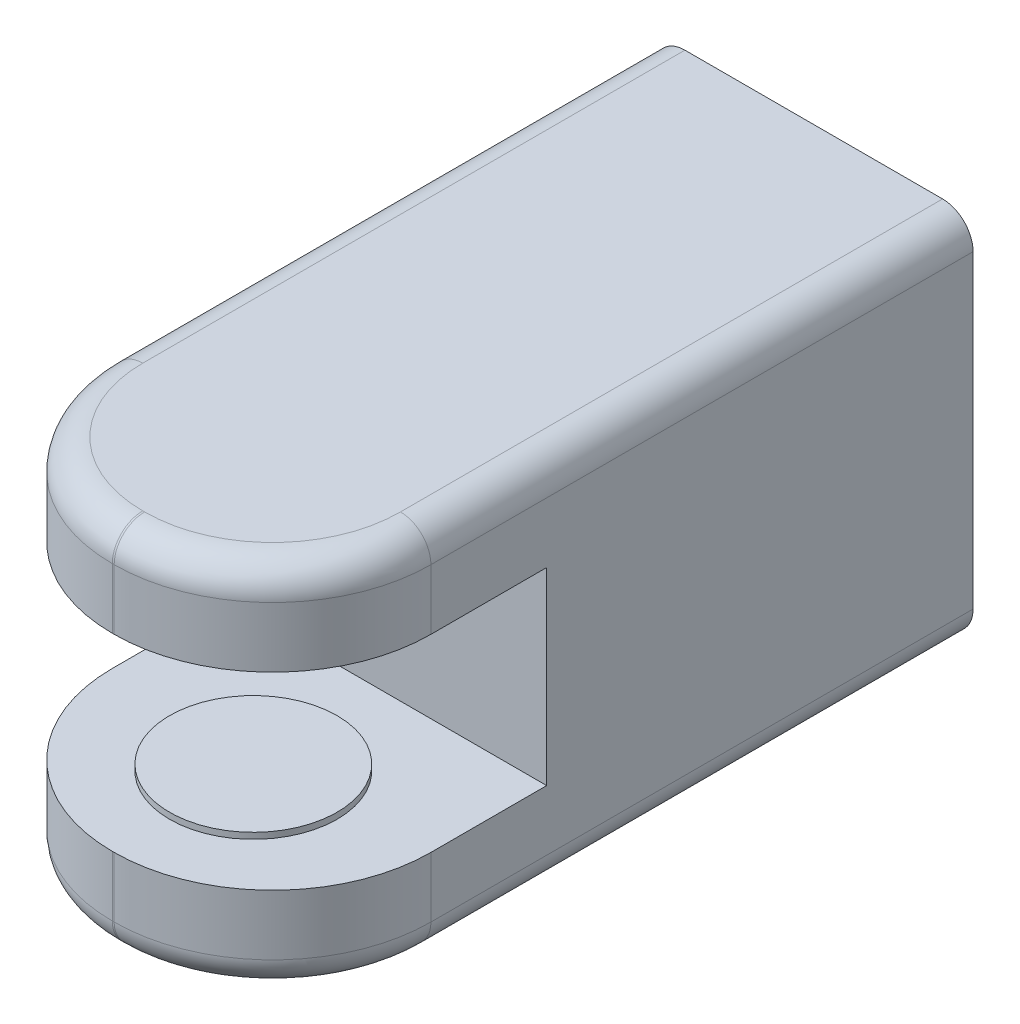
SolidWorks part; units mm, degrees
ref_plane "Piano frontale" through (0, 0, 0) normal (0, 0, 1) x (1, 0, 0)
ref_plane "Piano superiore" through (0, 0, 0) normal (0, 1, 0) x (1, 0, 0)
ref_plane "Piano destro" through (0, 0, 0) normal (1, 0, 0) x (0, 0, -1)
ref_plane "PianoContatto" through (0, 0, 0) normal (0, 0, 1) x (1, 0, 0)
sketch "Schizzo4" plane through (0, 0, 0) normal (0, 0, 1) x (1, 0, 0)
  circle A0 centre (0, 0) radius 38.5
  dimension "D1" = 77
extrude "CorpoContatto" add sketch "Schizzo4" along normal blind 3
sketch "Schizzo5" plane through (0, 0, 0) normal (0, 1, 0) x (1, 0, 0)
  line L1 (-38.5, -3) -> (38.5, -3) construction
  line L2 (52.305, -3) -> (-52.305, -3)
  line L3 (52.305, -3) -> (52.305, -181)
  line L4 (0.305, -233) -> (-0.305, -233)
  line L5 (-52.305, -3) -> (-52.305, -181)
  arc A0 (-0.305, -233) -> (-52.305, -181) centre (-0.305, -181) cw
  arc A1 (52.305, -181) -> (0.305, -233) centre (0.305, -181) cw
  point P6 (0, -3)
  point P12 (-52.305, -233)
  dimension "D3" = 52
  dimension "D1" = 104.61
  dimension "D2" = 230
extrude "CorpoRotante" add sketch "Schizzo5" along normal mid plane 121.61
fillet "Raccordo" radius 10 10 edges at (52.305, 60.805, 92) (37.0746, 60.805, 217.7696) (0, 60.805, 233) (-37.0746, 60.805, 217.7696) (52.305, -60.805, 92) (37.0746, -60.805, 217.7696) (0, -60.805, 233) (-37.0746, -60.805, 217.7696) (-52.305, 60.805, 92) (-52.305, -60.805, 92)
sketch "Schizzo6" plane through (0, 0, 0) normal (0, 1, 0) x (1, 0, 0)
  line L0 (-52.305, -3) -> (-52.305, -181) construction
  line L1 (-52.305, -143) -> (52.305, -143)
  line L2 (-52.305, -143) -> (-52.305, -233)
  line L3 (-52.305, -233) -> (52.305, -233)
  line L4 (52.305, -143) -> (52.305, -233)
  line L5 (52.305, -181) -> (52.305, -3) construction
  dimension "D1" = 90
extrude "TaglioCentrale" cut sketch "Schizzo6" against normal mid plane 62
sketch "Schizzo7" plane through (0, 31, 0) normal (0, -1, 0) x (1, 0, 0)
  line L0 (0, 0) -> (0, 187) construction
  circle A0 centre (0, 187) radius 27.5
  dimension "D2" = 55
  dimension "D1" = 187
extrude "Contatto" add sketch "Schizzo7" along normal blind 2
mirror "Specchia1" about plane through (0, 0, 0) normal (0, 1, 0) of "Contatto"
